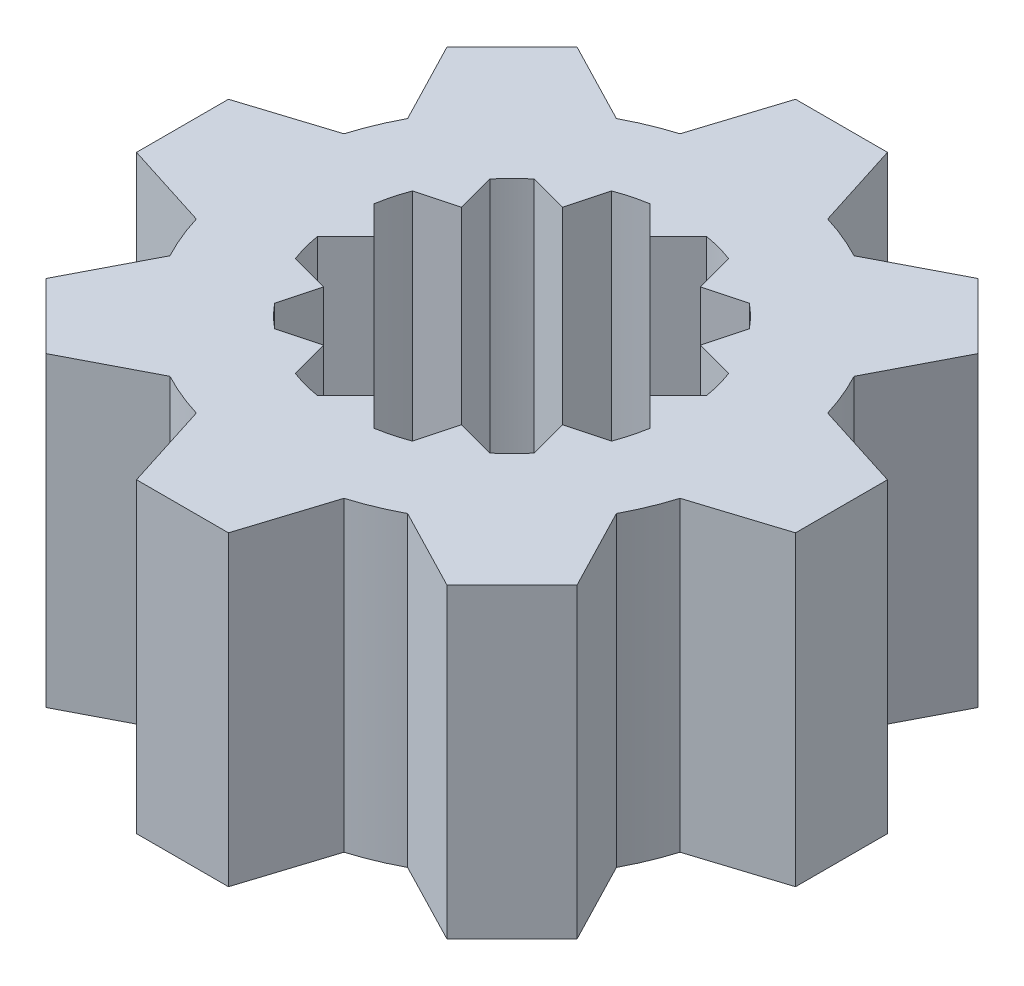
SolidWorks part; units mm, degrees
ref_plane "Front Plane" through (0, 0, 0) normal (0, 0, 1) x (1, 0, 0)
ref_plane "Top Plane" through (0, 0, 0) normal (0, 1, 0) x (1, 0, 0)
ref_plane "Right Plane" through (0, 0, 0) normal (1, 0, 0) x (0, 0, -1)
sketch "Sketch1" plane through (0, 0, 0) normal (0, 1, 0) x (1, 0, 0)
  line L0 (0, 5.5) -> (0, 4.5) construction
  line L1 (2.75, 4.7631) -> (2.25, 3.8971) construction
  line L2 (4.7631, 2.75) -> (3.8971, 2.25) construction
  line L3 (5.5, 0) -> (4.5, 0) construction
  line L4 (4.7631, -2.75) -> (3.8971, -2.25) construction
  line L5 (2.75, -4.7631) -> (2.25, -3.8971) construction
  line L6 (0, -5.5) -> (0, -4.5) construction
  line L7 (-2.75, -4.7631) -> (-2.25, -3.8971) construction
  line L8 (-4.7631, -2.75) -> (-3.8971, -2.25) construction
  line L9 (-5.5, 0) -> (-4.5, 0) construction
  line L10 (-4.7631, 2.75) -> (-3.8971, 2.25) construction
  line L11 (-2.75, 4.7631) -> (-2.25, 3.8971) construction
  line L12 (0, 4.5) -> (1, 5.5) construction
  line L13 (1, 5.5) -> (-1, 5.5) construction
  line L14 (-1, 5.5) -> (0, 4.5) construction
  line L15 (0, 4.5) -> (-0.9221, 5.4221)
  line L16 (0, 4.5) -> (0.9221, 5.4221)
  line L17 (2.25, 3.8971) -> (3.5097, 4.2346)
  line L18 (2.25, 3.8971) -> (1.9125, 5.1568)
  line L19 (3.8971, 2.25) -> (5.1568, 1.9125)
  line L20 (3.8971, 2.25) -> (4.2346, 3.5097)
  line L21 (4.5, 0) -> (5.4221, -0.9221)
  line L22 (4.5, 0) -> (5.4221, 0.9221)
  line L23 (3.8971, -2.25) -> (4.2346, -3.5097)
  line L24 (3.8971, -2.25) -> (5.1568, -1.9125)
  line L25 (2.25, -3.8971) -> (1.9125, -5.1568)
  line L26 (2.25, -3.8971) -> (3.5097, -4.2346)
  line L27 (0, -4.5) -> (-0.9221, -5.4221)
  line L28 (0, -4.5) -> (0.9221, -5.4221)
  line L29 (-2.25, -3.8971) -> (-3.5097, -4.2346)
  line L30 (-2.25, -3.8971) -> (-1.9125, -5.1568)
  line L31 (-3.8971, -2.25) -> (-5.1568, -1.9125)
  line L32 (-3.8971, -2.25) -> (-4.2346, -3.5097)
  line L33 (-4.5, 0) -> (-5.4221, 0.9221)
  line L34 (-4.5, 0) -> (-5.4221, -0.9221)
  line L35 (-3.8971, 2.25) -> (-4.2346, 3.5097)
  line L36 (-3.8971, 2.25) -> (-5.1568, 1.9125)
  line L37 (-2.25, 3.8971) -> (-1.9125, 5.1568)
  line L38 (-2.25, 3.8971) -> (-3.5097, 4.2346)
  line L39 (0, 8.25) -> (0, 10.75) construction
  line L40 (-1.5, 10.75) -> (1.5, 10.75)
  line L41 (-1.5, 10.75) -> (-2.4081, 7.8907)
  line L42 (1.5, 10.75) -> (2.4081, 7.8907)
  line L43 (6.5407, 8.6621) -> (3.8768, 7.2824)
  line L44 (6.5407, 8.6621) -> (8.6621, 6.5407)
  line L45 (8.6621, 6.5407) -> (7.2824, 3.8768)
  line L46 (10.75, 1.5) -> (7.8907, 2.4081)
  line L47 (10.75, 1.5) -> (10.75, -1.5)
  line L48 (10.75, -1.5) -> (7.8907, -2.4081)
  line L49 (8.6621, -6.5407) -> (7.2824, -3.8768)
  line L50 (8.6621, -6.5407) -> (6.5407, -8.6621)
  line L51 (6.5407, -8.6621) -> (3.8768, -7.2824)
  line L52 (1.5, -10.75) -> (2.4081, -7.8907)
  line L53 (1.5, -10.75) -> (-1.5, -10.75)
  line L54 (-1.5, -10.75) -> (-2.4081, -7.8907)
  line L55 (-6.5407, -8.6621) -> (-3.8768, -7.2824)
  line L56 (-6.5407, -8.6621) -> (-8.6621, -6.5407)
  line L57 (-8.6621, -6.5407) -> (-7.2824, -3.8768)
  line L58 (-10.75, -1.5) -> (-7.8907, -2.4081)
  line L59 (-10.75, -1.5) -> (-10.75, 1.5)
  line L60 (-10.75, 1.5) -> (-7.8907, 2.4081)
  line L61 (-8.6621, 6.5407) -> (-7.2824, 3.8768)
  line L62 (-8.6621, 6.5407) -> (-6.5407, 8.6621)
  line L63 (-6.5407, 8.6621) -> (-3.8768, 7.2824)
  circle A0 centre (0, 0) radius 2.75 construction
  circle A1 centre (0, 0) radius 5.5 construction
  arc A2 (0.9221, 5.4221) -> (1.9125, 5.1568) centre (0, 0) cw
  arc A3 (3.5097, 4.2346) -> (4.2346, 3.5097) centre (0, 0) cw
  arc A4 (5.4221, 0.9221) -> (5.1568, 1.9125) centre (0, 0) ccw
  arc A5 (5.1568, -1.9125) -> (5.4221, -0.9221) centre (0, 0) ccw
  arc A6 (3.5097, -4.2346) -> (4.2346, -3.5097) centre (0, 0) ccw
  arc A7 (0.9221, -5.4221) -> (1.9125, -5.1568) centre (0, 0) ccw
  arc A8 (-1.9125, -5.1568) -> (-0.9221, -5.4221) centre (0, 0) ccw
  arc A9 (-3.5097, -4.2346) -> (-4.2346, -3.5097) centre (0, 0) cw
  arc A10 (-5.1568, -1.9125) -> (-5.4221, -0.9221) centre (0, 0) cw
  arc A11 (-5.4221, 0.9221) -> (-5.1568, 1.9125) centre (0, 0) cw
  arc A12 (-4.2346, 3.5097) -> (-3.5097, 4.2346) centre (0, 0) cw
  arc A13 (-0.9221, 5.4221) -> (-1.9125, 5.1568) centre (0, 0) ccw
  circle A14 centre (0, 0) radius 8.25 construction
  arc A15 (2.4081, 7.8907) -> (3.8768, 7.2824) centre (0, 0) cw
  arc A16 (7.2824, 3.8768) -> (7.8907, 2.4081) centre (0, 0) cw
  arc A17 (7.8907, -2.4081) -> (7.2824, -3.8768) centre (0, 0) cw
  arc A18 (3.8768, -7.2824) -> (2.4081, -7.8907) centre (0, 0) cw
  arc A19 (-2.4081, -7.8907) -> (-3.8768, -7.2824) centre (0, 0) cw
  arc A20 (-7.2824, -3.8768) -> (-7.8907, -2.4081) centre (0, 0) cw
  arc A21 (-7.8907, 2.4081) -> (-7.2824, 3.8768) centre (0, 0) cw
  arc A22 (-3.8768, 7.2824) -> (-2.4081, 7.8907) centre (0, 0) cw
  point P31 (0, 0)
  point P71 (0, 10.75)
  point P105 (0, 0)
  dimension "D1" = 5.5
  dimension "D2" = 11
  dimension "D5" = 16.5
  dimension "D4" = 1
  dimension "D6" = 2.5
  dimension "D7" = 3
  dimension "D8" = 3
  dimension "D3" = 12
  dimension "D9" = 8
extrude "Boss-Extrude1" add sketch "Sketch1" along normal blind 10
